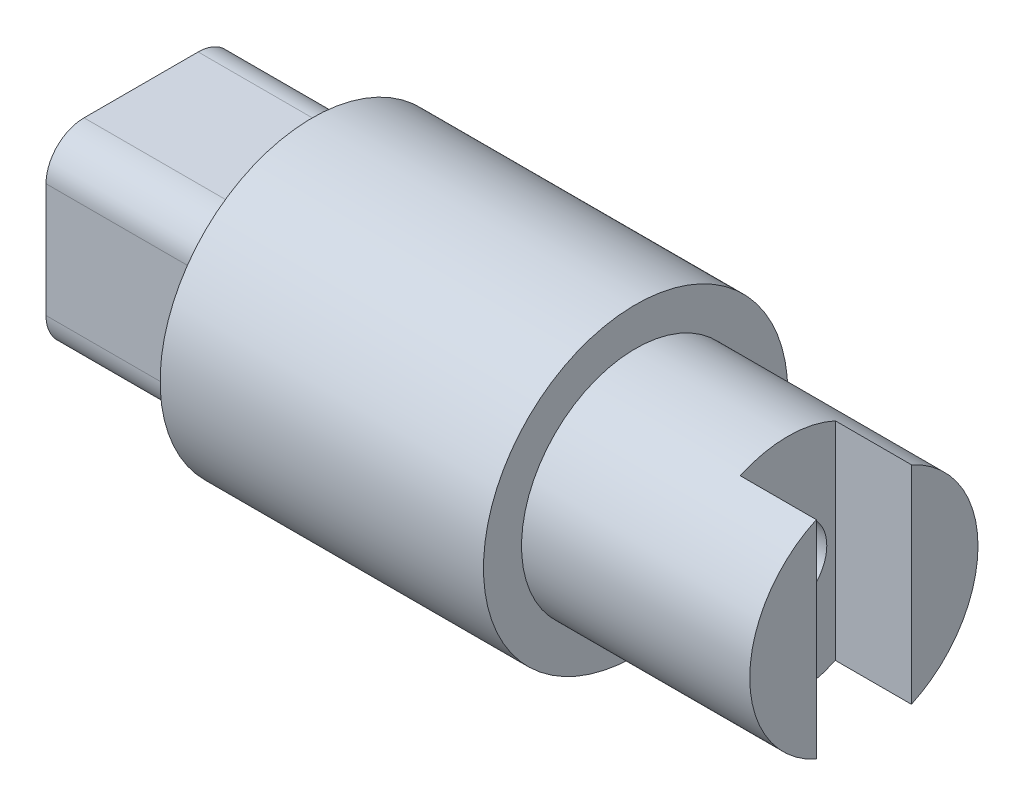
SolidWorks part; units mm, degrees
material "Plain Carbon Steel"
ref_plane "Front Plane" through (0, 0, 0) normal (0, 0, 1) x (1, 0, 0)
ref_plane "Top Plane" through (0, 0, 0) normal (0, 1, 0) x (1, 0, 0)
ref_plane "Right Plane" through (0, 0, 0) normal (1, 0, 0) x (0, 0, -1)
sketch "Sketch1" plane through (0, 0, 0) normal (0, 0, 1) x (1, 0, 0)
  line L0 (5, 4) -> (5, 0)
  line L1 (5, 0) -> (13.5, 0)
  line L2 (13.5, 0) -> (13.5, 4)
  line L3 (13.5, 4) -> (5, 4)
  line L4 (5, 0) -> (13.5, 0) construction
  dimension "D1" = 8.5
revolve "Revolve1" add sketch "Sketch1" angle 360 about L4
sketch "Sketch2" plane through (5, 0, 0) normal (-1, 0, 0) x (0, 0, 1)
  line L1 (-2.5, -2.5) -> (2.5, -2.5)
  line L2 (-2.5, -2.5) -> (-2.5, 2.5)
  line L3 (-2.5, 2.5) -> (2.5, 2.5)
  line L4 (2.5, -2.5) -> (2.5, 2.5)
  line L5 (-2.5, -2.5) -> (2.5, 2.5) construction
  line L6 (-2.5, 2.5) -> (2.5, -2.5) construction
  point P0 (0, 0)
  dimension "D1" = 5
extrude "Boss-Extrude1" add sketch "Sketch2" along normal blind 4.5
sketch "Sketch3" plane through (13.5, 0, 0) normal (1, 0, 0) x (0, 0, -1)
  circle A0 centre (0, 0) radius 3
  dimension "D1" = 6
extrude "Boss-Extrude2" add sketch "Sketch3" along normal blind 6
sketch "Sketch8" plane through (19.5, 0, 0) normal (1, 0, 0) x (0, 0, -1)
  line L1 (-1.25, -3.4199) -> (1.25, -3.4199)
  line L2 (-1.25, -3.4199) -> (-1.25, 3.4199)
  line L3 (-1.25, 3.4199) -> (1.25, 3.4199)
  line L4 (1.25, -3.4199) -> (1.25, 3.4199)
  line L5 (-1.25, -3.4199) -> (1.25, 3.4199) construction
  line L6 (-1.25, 3.4199) -> (1.25, -3.4199) construction
  point P0 (0, 0)
  dimension "D1" = 2.5
extrude "Cut-Extrude2" cut sketch "Sketch8" against normal blind 2
sketch "Sketch7" plane through (0.5, 0, 0) normal (-1, 0, 0) x (0, 0, 1)
  circle A0 centre (0, 0) radius 0.5
  dimension "D1" = 1
fillet "Fillet1" radius 1 4 edges at (2.75, -2.5, -2.5) (2.75, -2.5, 2.5) (2.75, 2.5, 2.5) (2.75, 2.5, -2.5)
hole_wizard "M3x0.5 Tapped Hole1" positions "3DSketch3" profile "Sketch11" tap size "M3x0.5" standard "ANSI Metric"
sketch3d "3DSketch3"
  point P0 (0.5, 0, 0)
sketch "Sketch11" plane through (0.5, 0, 0) normal (0, 1, 0) x (0, 0, 1)
  line L0 (0, 0) -> (0, 8.2511)
  line L1 (0, 8.2511) -> (1.25, 7.5)
  line L2 (1.25, 7.5) -> (1.25, 0)
  line L5 (1.25, 0) -> (0, 0)
  line L10 (0, 8.2511) -> (-1.25, 7.5) construction
  line L11 (0, -6.35) -> (0, 107.95) construction
  dimension "Tap Drill Dia." = 2.5
  dimension "Tap Drill Depth" = 7.5
  dimension "Drill Angle" = 118
sketch "Sketch12" plane through (17.5, 0, 0) normal (1, 0, 0) x (0, 0, -1)
  point P0 (0, 0)
hole_wizard "M2.5x0.45 Tapped Hole2" positions "3DSketch4" profile "Sketch13" tap size "M2.5x0.45" standard "ANSI Metric"
sketch3d "3DSketch4"
  point P0 (17.5, 0, 0)
sketch "Sketch13" plane through (17.5, 0, 0) normal (0, 1, 0) x (0, 0, -1)
  line L0 (0, 0) -> (0, 5.6159)
  line L1 (0, 5.6159) -> (1.025, 5)
  line L2 (1.025, 5) -> (1.025, 0)
  line L5 (1.025, 0) -> (0, 0)
  line L10 (0, 5.6159) -> (-1.025, 5) construction
  line L11 (0, -6.35) -> (0, 107.95) construction
  dimension "Tap Drill Dia." = 2.05
  dimension "Tap Drill Depth" = 5
  dimension "Drill Angle" = 118
